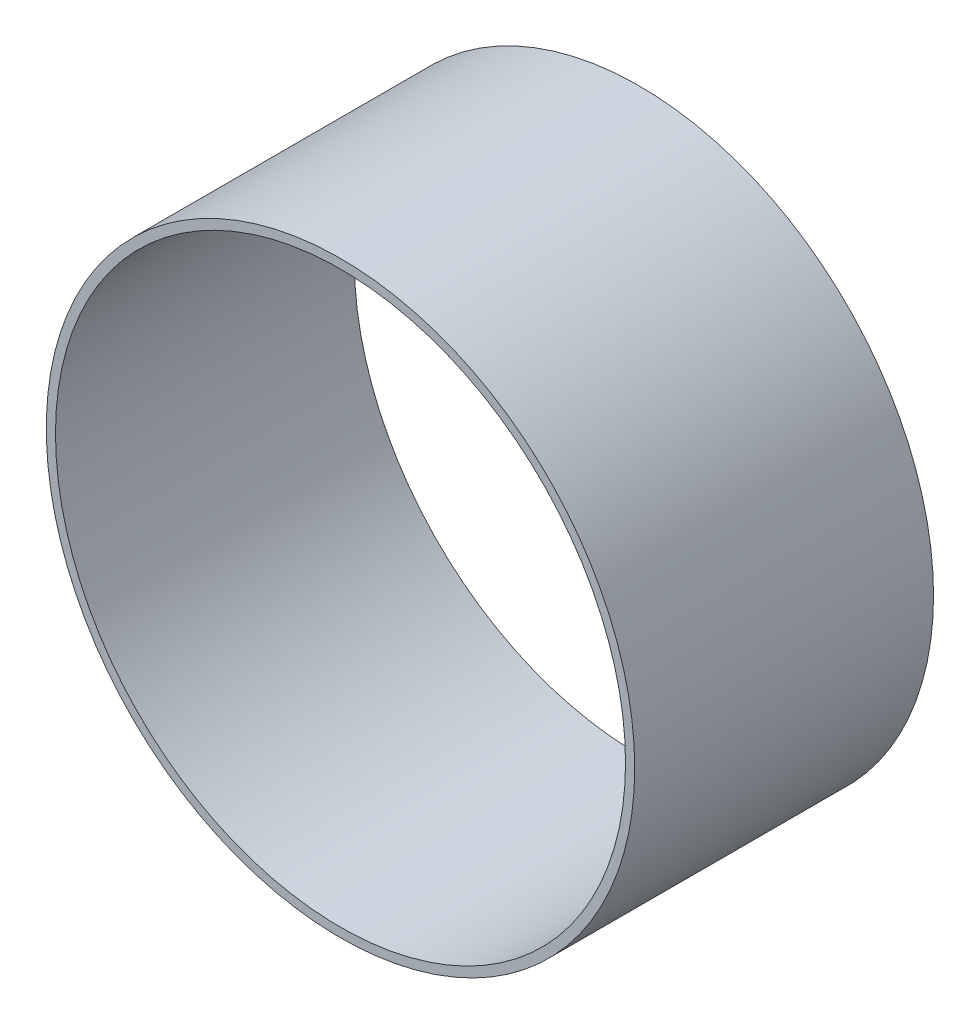
SolidWorks part; units mm, degrees
ref_plane "Спереди" through (0, 0, 0) normal (0, 0, 1) x (1, 0, 0)
ref_plane "Сверху" through (0, 0, 0) normal (0, 1, 0) x (1, 0, 0)
ref_plane "Справа" through (0, 0, 0) normal (1, 0, 0) x (0, 0, -1)
sketch "Эскиз1" plane through (0, 0, 0) normal (0, 0, 1) x (1, 0, 0)
  circle A0 centre (0, 0) radius 64
  circle A1 centre (0, 0) radius 62
extrude "Printed_fixed_case" add sketch "Эскиз1" along normal blind 65 from offset 32
